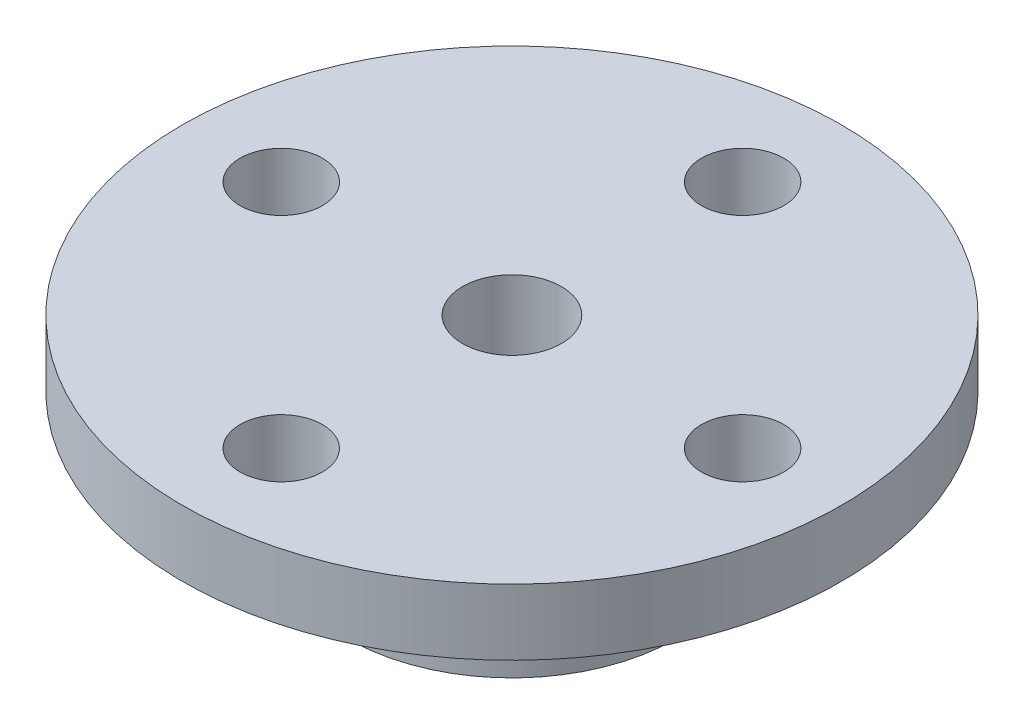
SolidWorks part; units mm, degrees
material "1060 合金"
ref_plane "前视" through (0, 0, 0) normal (0, 0, 1) x (1, 0, 0)
ref_plane "上视" through (0, 0, 0) normal (0, 1, 0) x (1, 0, 0)
ref_plane "右视" through (0, 0, 0) normal (1, 0, 0) x (0, 0, -1)
sketch "草图1" plane through (0, 0, 0) normal (0, 0, 1) x (1, 0, 0)
  line L0 (0, 0) -> (0, -9.9107) construction
  line L1 (10, 0) -> (1.5, 0)
  line L2 (1.5, 0) -> (1.5, -3)
  line L3 (1.5, -3) -> (3, -3)
  line L4 (3, -3) -> (3, -6)
  line L6 (10, 0) -> (10, -2)
  line L7 (10, -2) -> (5, -2)
  line L8 (5, -2) -> (5, -6)
  line L9 (5, -6) -> (3, -6)
  dimension "D1" = 3
  dimension "D2" = 20
  dimension "D3" = 2
  dimension "D4" = 6
  dimension "D5" = 6
  dimension "D6" = 10
  dimension "D7" = 3
revolve "旋转1" add sketch "草图1" angle 360 about L0
hole_wizard "M3 螺纹孔1" positions "草图3" profile "草图2" tap size "M3" standard "GB" end condition through all
sketch "草图3" plane through (0, -2, 0) normal (0, -1, 0) x (-1, 0, 0)
  circle A0 centre (0, 0) radius 7 construction
  point P0 (7, 0)
  point P2 (0, -7)
  point P4 (-7, 0)
  point P6 (0, 7)
  dimension "D1" = 14
sketch "草图2" plane through (-7, -2, 0) normal (1, 0, 0) x (0, 0, -1)
  line L0 (0, 0) -> (0, 2)
  line L1 (0, 2) -> (1.25, 2)
  line L2 (1.25, 2) -> (1.25, 0)
  line L5 (1.25, 0) -> (0, 0)
  line L11 (0, -6.35) -> (0, 107.95) construction
  dimension "通孔螺纹孔钻头直径" = 2.5
  dimension "通孔螺纹孔钻头深度" = 2
cosmetic thread "孔螺蚊线1" parameters "D2"=3
cosmetic thread "孔螺蚊线2" parameters "D2"=3
cosmetic thread "孔螺蚊线3" parameters "D2"=3
cosmetic thread "孔螺蚊线4" parameters "D2"=3
